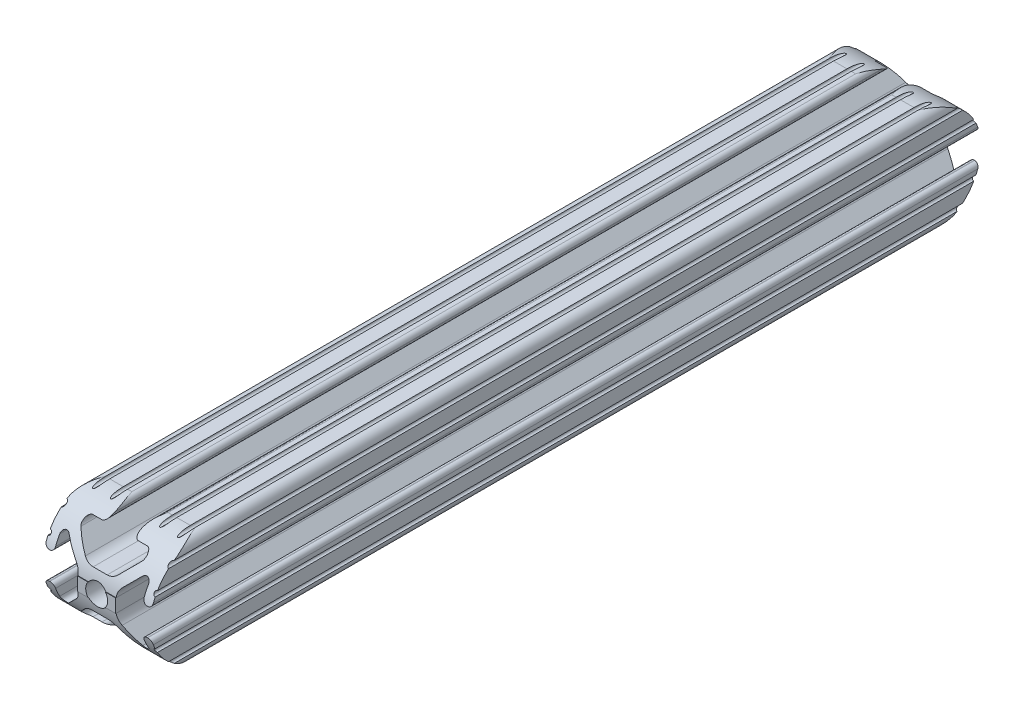
SolidWorks part; units mm, degrees
material "6061 Alloy"
ref_plane "Front Plane" through (0, 0, 0) normal (0, 0, 1) x (1, 0, 0)
ref_plane "Top Plane" through (0, 0, 0) normal (0, 1, 0) x (1, 0, 0)
ref_plane "Right Plane" through (0, 0, 0) normal (1, 0, 0) x (0, 0, -1)
sketch "Sketch1" plane through (0, 0, 0) normal (0, 0, 1) x (1, 0, 0)
  line L88 (-7.1797, -8.6452) -> (-3.9523, -5.4237)
  line L89 (-1.7093, -4.4958) -> (1.7093, -4.4958)
  line L90 (3.9523, -5.4237) -> (7.1797, -8.6452)
  line L91 (6.4164, -10.4902) -> (4.2875, -10.4902)
  line L92 (3.2385, -11.5392) -> (3.2385, -11.651)
  line L93 (4.2875, -12.7) -> (5.3171, -12.7)
  line L94 (6.3331, -12.7) -> (9.5504, -12.7)
  line L95 (12.7, -9.5504) -> (12.7, -6.3331)
  line L96 (12.7, -5.3171) -> (12.7, -4.2875)
  line L97 (11.651, -3.2385) -> (11.5392, -3.2385)
  line L98 (10.4902, -4.2875) -> (10.4902, -6.4021)
  line L99 (8.7371, -7.1294) -> (5.441, -3.8408)
  line L100 (4.5085, -1.5932) -> (4.5085, 1.5932)
  line L101 (5.441, 3.8408) -> (8.7371, 7.1294)
  line L102 (10.4902, 6.4021) -> (10.4902, 4.2875)
  line L103 (11.5392, 3.2385) -> (11.651, 3.2385)
  line L104 (12.7, 4.2875) -> (12.7, 5.3171)
  line L105 (12.7, 6.3331) -> (12.7, 9.5504)
  line L106 (9.5504, 12.7) -> (6.3331, 12.7)
  line L107 (5.3171, 12.7) -> (4.2875, 12.7)
  line L108 (3.2385, 11.651) -> (3.2385, 11.5392)
  line L109 (4.2875, 10.4902) -> (6.4768, 10.4902)
  line L110 (7.207, 8.7244) -> (3.8983, 5.4232)
  line L111 (1.6558, 4.4958) -> (-1.6558, 4.4958)
  line L112 (-3.8983, 5.4232) -> (-7.207, 8.7244)
  line L113 (-6.4768, 10.4902) -> (-4.2875, 10.4902)
  line L114 (-3.2385, 11.5392) -> (-3.2385, 11.651)
  line L115 (-4.2875, 12.7) -> (-5.3171, 12.7)
  line L116 (-6.3331, 12.7) -> (-9.5504, 12.7)
  line L117 (-12.7, 9.5504) -> (-12.7, 6.3331)
  line L118 (-12.7, 5.3171) -> (-12.7, 4.2875)
  line L119 (-11.651, 3.2385) -> (-11.5392, 3.2385)
  line L120 (-10.4902, 4.2875) -> (-10.4902, 6.4021)
  line L121 (-8.7371, 7.1294) -> (-5.441, 3.8408)
  line L122 (-4.5085, 1.5932) -> (-4.5085, -1.5932)
  line L123 (-5.441, -3.8408) -> (-8.7371, -7.1294)
  line L124 (-10.4902, -6.4021) -> (-10.4902, -4.2875)
  line L125 (-11.5392, -3.2385) -> (-11.651, -3.2385)
  line L126 (-12.7, -4.2875) -> (-12.7, -5.3171)
  line L127 (-12.7, -6.3331) -> (-12.7, -9.5504)
  line L128 (-9.5504, -12.7) -> (-6.3331, -12.7)
  line L129 (-5.3171, -12.7) -> (-4.2875, -12.7)
  line L130 (-3.2385, -11.651) -> (-3.2385, -11.5392)
  line L131 (-4.2875, -10.4902) -> (-6.4164, -10.4902)
  circle A1 centre (0, 0) radius 2.6035
  arc A104 (-7.1797, -8.6452) -> (-6.4164, -10.4902) centre (-6.4164, -9.4098) ccw
  arc A105 (-1.7093, -4.4958) -> (-3.9523, -5.4237) centre (-1.7093, -7.6708) ccw
  arc A106 (3.9523, -5.4237) -> (1.7093, -4.4958) centre (1.7093, -7.6708) ccw
  arc A107 (6.4164, -10.4902) -> (7.1797, -8.6452) centre (6.4164, -9.4098) ccw
  arc A108 (4.2875, -10.4902) -> (3.2385, -11.5392) centre (4.2875, -11.5392) ccw
  arc A109 (3.2385, -11.651) -> (4.2875, -12.7) centre (4.2875, -11.651) ccw
  arc A110 (6.3331, -12.7) -> (5.3171, -12.7) centre (5.8251, -12.7) ccw
  arc A111 (10.5664, -12.6998) -> (9.5504, -12.7) centre (10.0584, -12.7) ccw
  arc A112 (10.5664, -12.6998) -> (12.6998, -10.5664) centre (10.5918, -10.5918) ccw
  arc A113 (12.7, -9.5504) -> (12.6998, -10.5664) centre (12.7, -10.0584) ccw
  arc A114 (12.7, -5.3171) -> (12.7, -6.3331) centre (12.7, -5.8251) ccw
  arc A115 (12.7, -4.2875) -> (11.651, -3.2385) centre (11.651, -4.2875) ccw
  arc A116 (11.5392, -3.2385) -> (10.4902, -4.2875) centre (11.5392, -4.2875) ccw
  arc A117 (8.7371, -7.1294) -> (10.4902, -6.4021) centre (9.4628, -6.4021) ccw
  arc A118 (4.5085, -1.5932) -> (5.441, -3.8408) centre (7.6835, -1.5932) ccw
  arc A119 (5.441, 3.8408) -> (4.5085, 1.5932) centre (7.6835, 1.5932) ccw
  arc A120 (10.4902, 6.4021) -> (8.7371, 7.1294) centre (9.4628, 6.4021) ccw
  arc A121 (10.4902, 4.2875) -> (11.5392, 3.2385) centre (11.5392, 4.2875) ccw
  arc A122 (11.651, 3.2385) -> (12.7, 4.2875) centre (11.651, 4.2875) ccw
  arc A123 (12.7, 6.3331) -> (12.7, 5.3171) centre (12.7, 5.8251) ccw
  arc A124 (12.6998, 10.5664) -> (12.7, 9.5504) centre (12.7, 10.0584) ccw
  arc A125 (12.6998, 10.5664) -> (10.5664, 12.6998) centre (10.5918, 10.5918) ccw
  arc A126 (9.5504, 12.7) -> (10.5664, 12.6998) centre (10.0584, 12.7) ccw
  arc A127 (5.3171, 12.7) -> (6.3331, 12.7) centre (5.8251, 12.7) ccw
  arc A128 (4.2875, 12.7) -> (3.2385, 11.651) centre (4.2875, 11.651) ccw
  arc A129 (3.2385, 11.5392) -> (4.2875, 10.4902) centre (4.2875, 11.5392) ccw
  arc A130 (7.207, 8.7244) -> (6.4768, 10.4902) centre (6.4768, 9.4563) ccw
  arc A131 (1.6558, 4.4958) -> (3.8983, 5.4232) centre (1.6558, 7.6708) ccw
  arc A132 (-3.8983, 5.4232) -> (-1.6558, 4.4958) centre (-1.6558, 7.6708) ccw
  arc A133 (-6.4768, 10.4902) -> (-7.207, 8.7244) centre (-6.4768, 9.4563) ccw
  arc A134 (-4.2875, 10.4902) -> (-3.2385, 11.5392) centre (-4.2875, 11.5392) ccw
  arc A135 (-3.2385, 11.651) -> (-4.2875, 12.7) centre (-4.2875, 11.651) ccw
  arc A136 (-6.3331, 12.7) -> (-5.3171, 12.7) centre (-5.8251, 12.7) ccw
  arc A137 (-10.5664, 12.6998) -> (-9.5504, 12.7) centre (-10.0584, 12.7) ccw
  arc A138 (-10.5664, 12.6998) -> (-12.6998, 10.5664) centre (-10.5918, 10.5918) ccw
  arc A139 (-12.7, 9.5504) -> (-12.6998, 10.5664) centre (-12.7, 10.0584) ccw
  arc A140 (-12.7, 5.3171) -> (-12.7, 6.3331) centre (-12.7, 5.8251) ccw
  arc A141 (-12.7, 4.2875) -> (-11.651, 3.2385) centre (-11.651, 4.2875) ccw
  arc A142 (-11.5392, 3.2385) -> (-10.4902, 4.2875) centre (-11.5392, 4.2875) ccw
  arc A143 (-8.7371, 7.1294) -> (-10.4902, 6.4021) centre (-9.4628, 6.4021) ccw
  arc A144 (-4.5085, 1.5932) -> (-5.441, 3.8408) centre (-7.6835, 1.5932) ccw
  arc A145 (-5.441, -3.8408) -> (-4.5085, -1.5932) centre (-7.6835, -1.5932) ccw
  arc A146 (-10.4902, -6.4021) -> (-8.7371, -7.1294) centre (-9.4628, -6.4021) ccw
  arc A147 (-10.4902, -4.2875) -> (-11.5392, -3.2385) centre (-11.5392, -4.2875) ccw
  arc A148 (-11.651, -3.2385) -> (-12.7, -4.2875) centre (-11.651, -4.2875) ccw
  arc A149 (-12.7, -6.3331) -> (-12.7, -5.3171) centre (-12.7, -5.8251) ccw
  arc A150 (-12.6998, -10.5664) -> (-12.7, -9.5504) centre (-12.7, -10.0584) ccw
  arc A151 (-12.6998, -10.5664) -> (-10.5664, -12.6998) centre (-10.5918, -10.5918) ccw
  arc A152 (-9.5504, -12.7) -> (-10.5664, -12.6998) centre (-10.0584, -12.7) ccw
  arc A153 (-5.3171, -12.7) -> (-6.3331, -12.7) centre (-5.8251, -12.7) ccw
  arc A154 (-4.2875, -12.7) -> (-3.2385, -11.651) centre (-4.2875, -11.651) ccw
  arc A155 (-3.2385, -11.5392) -> (-4.2875, -10.4902) centre (-4.2875, -11.5392) ccw
extrude "Boss-Extrude1" add sketch "Sketch1" along normal mid plane 196.85
sketch "Sketch2" plane through (4.5085, 0, 0) normal (1, 0, 0) x (0, 0, -1)
  line L0 (-98.425, -1.5932) -> (-98.425, 1.5932) construction
  line L1 (-98.425, -12.6998) -> (98.425, -12.6998) construction
  line L2 (-98.425, 0) -> (-98.425, -12.7)
  line L3 (-98.425, -12.7) -> (-85.725, -12.7)
  line L4 (-98.425, -12.7) -> (98.425, -12.7) construction
  line L5 (-98.425, 12.6998) -> (98.425, 12.6998) construction
  line L6 (-85.7872, 12.6998) -> (-98.425, 12.7) construction
  line L7 (-98.425, 12.7) -> (-98.425, 0)
  line L8 (-98.425, 12.7) -> (98.425, 12.7) construction
  line L9 (-98.425, 12.7) -> (-98.425, 13.97)
  line L10 (-98.425, 13.97) -> (-85.7872, 13.97)
  line L11 (-85.7872, 13.97) -> (-85.7872, 12.6998)
  circle A0 centre (-85.725, 0) radius 3.175
  circle A1 centre (-60.325, 0) radius 3.175
  arc A2 (-98.425, 0) -> (-85.725, -12.7) centre (-85.725, 0) ccw
  arc A3 (-98.425, 0) -> (-85.7872, 12.6998) centre (-85.725, 0) cw
  line M4 (98.425, 1.5932) -> (-98.425, 1.5932)
  line M6 (-98.425, -1.5932) -> (98.425, -1.5932)
  dimension "D1" = 6.35
  dimension "D2" = 12.7
  dimension "D3" = 12.6998
  dimension "D4" = 25.4
  dimension "D5" = 1.27
extrude "Cut-Extrude1" cut sketch "Sketch2" against normal through all both and the other way through all contours A3 L6 L7 M4 | A2 L2 L3 M6 | A0 M4 M6 | A1 M4 M6 | A1 M4 | A1 M6 | A0 M6 | A0 M4 | L6 L11 L10 L9
sketch "Sketch3" plane through (4.5085, 0, 0) normal (1, 0, 0) x (0, 0, -1)
  line L0 (98.425, 6.3331) -> (98.425, 9.5504) construction
  line L1 (98.425, -1.5932) -> (98.425, 1.5932) construction
  line L2 (-85.7872, 12.7) -> (98.425, 12.7) construction
  line L3 (85.725, 12.7) -> (98.425, 12.7)
  line L4 (98.425, 12.7) -> (98.425, -12.7)
  line L5 (98.425, -12.7) -> (85.725, -12.7)
  circle A0 centre (85.725, 0) radius 12.7 construction
  arc A1 (85.725, 12.7) -> (85.725, -12.7) centre (85.725, 0) cw
  line M2 (98.425, 1.5932) -> (-57.5787, 1.5932)
  line M4 (-57.5787, -1.5932) -> (98.425, -1.5932)
  dimension "D1" = 12.7
extrude "Cut-Extrude2" cut sketch "Sketch3" against normal through all both and the other way through all contours L3 A1 L4 M2 | A1 L5 L4 M4
